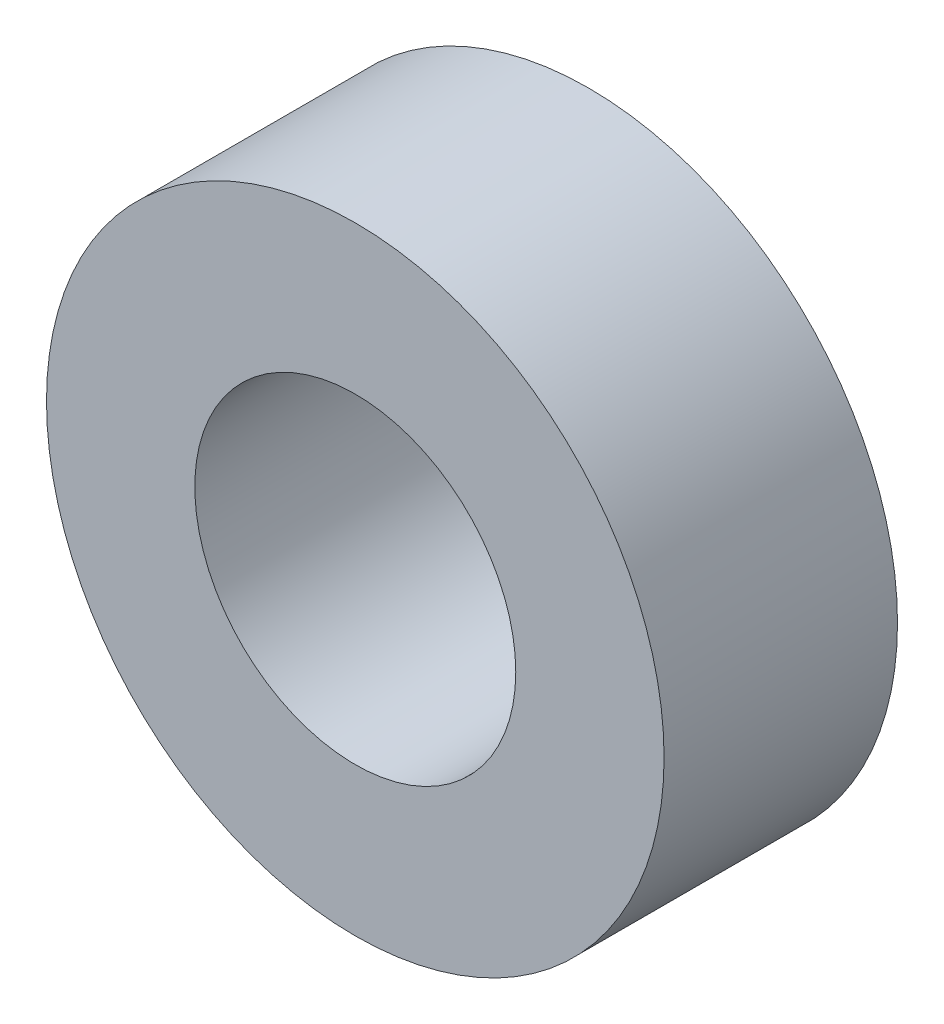
SolidWorks part; units mm, degrees
ref_plane "前视基准面" through (0, 0, 0) normal (0, 0, 1) x (1, 0, 0)
ref_plane "上视基准面" through (0, 0, 0) normal (0, 1, 0) x (1, 0, 0)
ref_plane "右视基准面" through (0, 0, 0) normal (1, 0, 0) x (0, 0, -1)
sketch "草图1" plane through (0, 0, 0) normal (0, 0, 1) x (1, 0, 0)
  circle A0 centre (0, 0) radius 3.175
  dimension "D1" = 6.35
extrude "金属件无牙型包络" add sketch "草图1" along normal blind 2.4
sketch "草图2" plane through (0, 0, 0) normal (0, 0, 1) x (1, 0, 0)
  circle A0 centre (0, 0) radius 1.65
  dimension "D1" = 3.3
extrude "内孔_装配间隙" cut sketch "草图2" along normal blind 2.4
